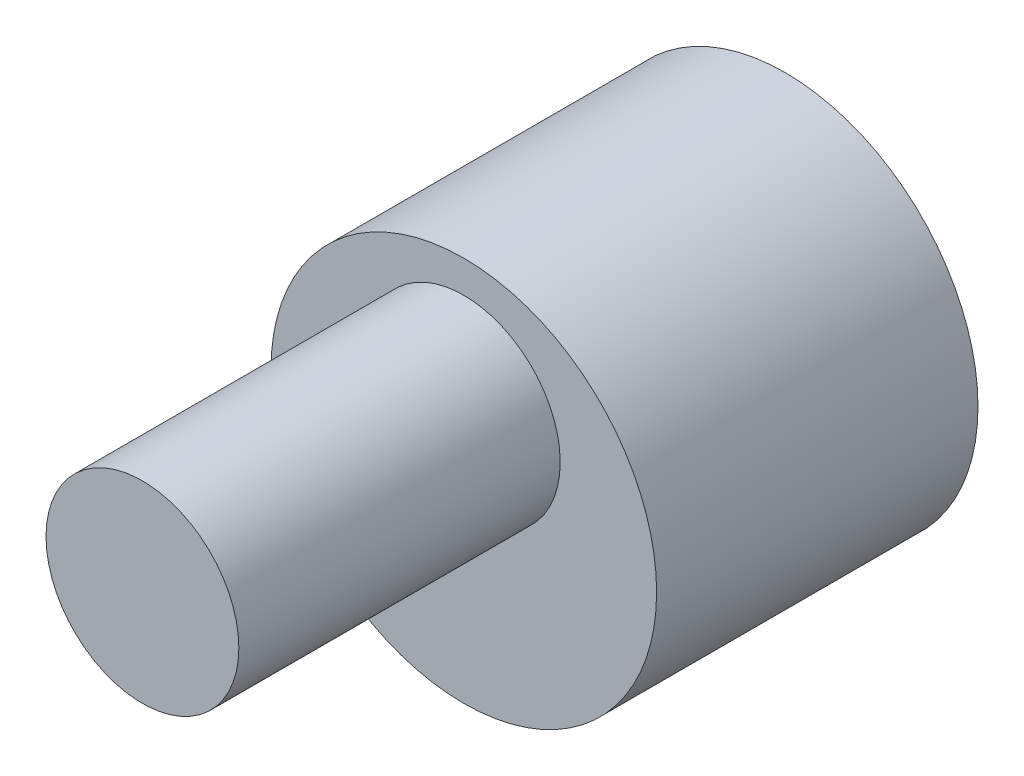
SolidWorks part; units mm, degrees
ref_plane "Front" through (0, 0, 0) normal (0, 0, 1) x (1, 0, 0)
ref_plane "Top" through (0, 0, 0) normal (0, 1, 0) x (1, 0, 0)
ref_plane "Right" through (0, 0, 0) normal (1, 0, 0) x (0, 0, -1)
sketch "Esquisse1" plane through (0, 0, 0) normal (0, 0, 1) x (1, 0, 0)
  circle A0 centre (0, 0) radius 6
  dimension "D1" = 12
extrude "Boss.-Extru.1" add sketch "Esquisse1" along normal blind 10
sketch "Esquisse2" plane through (0, 0, 10) normal (0, 0, 1) x (1, 0, 0)
  line L0 (0, 0) -> (0, 2) construction
  circle A0 centre (0, 2) radius 3
  point P5 (0.1347, 1.2795)
  dimension "D1" = 6
  dimension "D2" = 2
extrude "Boss.-Extru.2" add sketch "Esquisse2" along normal blind 10
